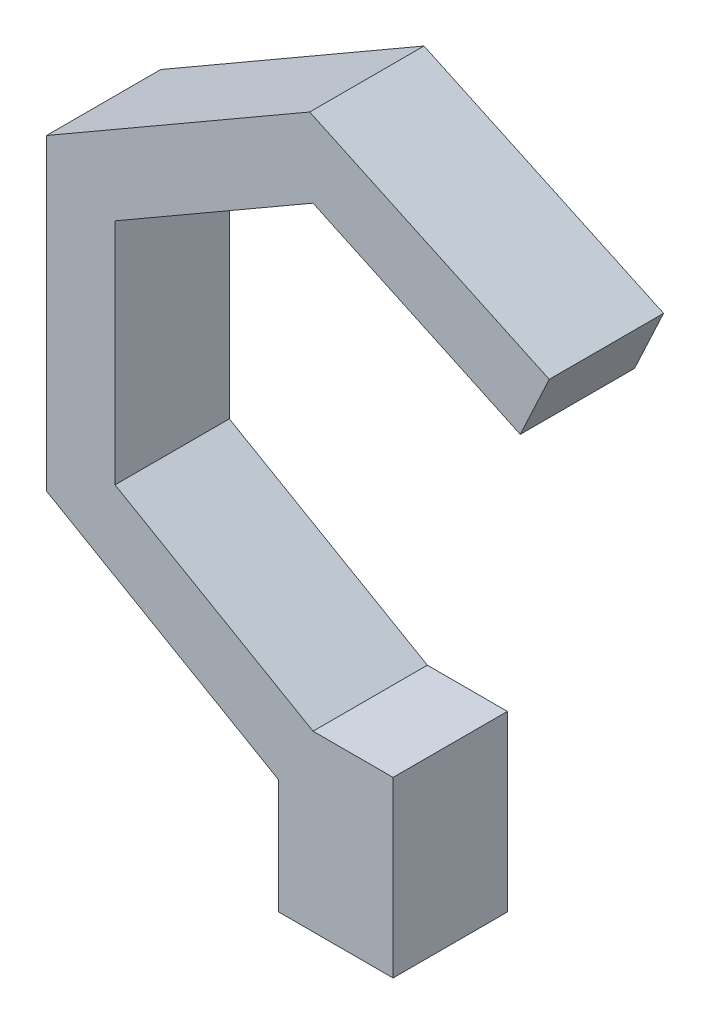
SolidWorks part; units mm, degrees
ref_plane "Front Plane" through (0, 0, 0) normal (0, 0, 1) x (1, 0, 0)
ref_plane "Top Plane" through (0, 0, 0) normal (0, 1, 0) x (1, 0, 0)
ref_plane "Right Plane" through (0, 0, 0) normal (1, 0, 0) x (0, 0, -1)
sketch "Sketch2" plane through (0, 0, 0) normal (0, 0, 1) x (1, 0, 0)
  line L0 (0, 0) -> (0, -25.4) construction
  line L1 (0, -25.4) -> (-21.997, -12.7)
  line L2 (-21.997, -12.7) -> (-21.997, 12.7)
  line L3 (-21.997, 12.7) -> (0, 25.4)
  line L4 (0, 25.4) -> (23.0202, 14.6655)
  line L5 (-3.81, -31.9991) -> (-29.617, -17.0994)
  line L6 (-29.617, -17.0994) -> (-29.617, 17.0994)
  line L7 (-29.617, 17.0994) -> (-0.3747, 33.9825)
  line L8 (-0.3747, 33.9825) -> (26.2406, 21.5716)
  line L9 (26.2406, 21.5716) -> (23.0202, 14.6655)
  line L10 (-3.81, -31.9991) -> (-3.81, -44.6991)
  line L11 (-3.81, -44.6991) -> (8.89, -44.6991)
  line L12 (0, -25.4) -> (8.89, -25.4)
  line L13 (8.89, -25.4) -> (8.89, -44.6991)
  circle A0 centre (0, 0) radius 15.875 construction
  point P3 (0, 0)
  dimension "D1" = 31.75
  dimension "D2" = 25.4
  dimension "D3" = 25.4
  dimension "D4" = 25.4
  dimension "D5" = 25.4
  dimension "D6" = 25.4
  dimension "D7" = 25.4
  dimension "D8" = 125
  dimension "D10" = 12.7
  dimension "D9" = 7.62
  dimension "D11" = 12.7
extrude "Boss-Extrude1" add sketch "Sketch2" along normal blind 12.7
